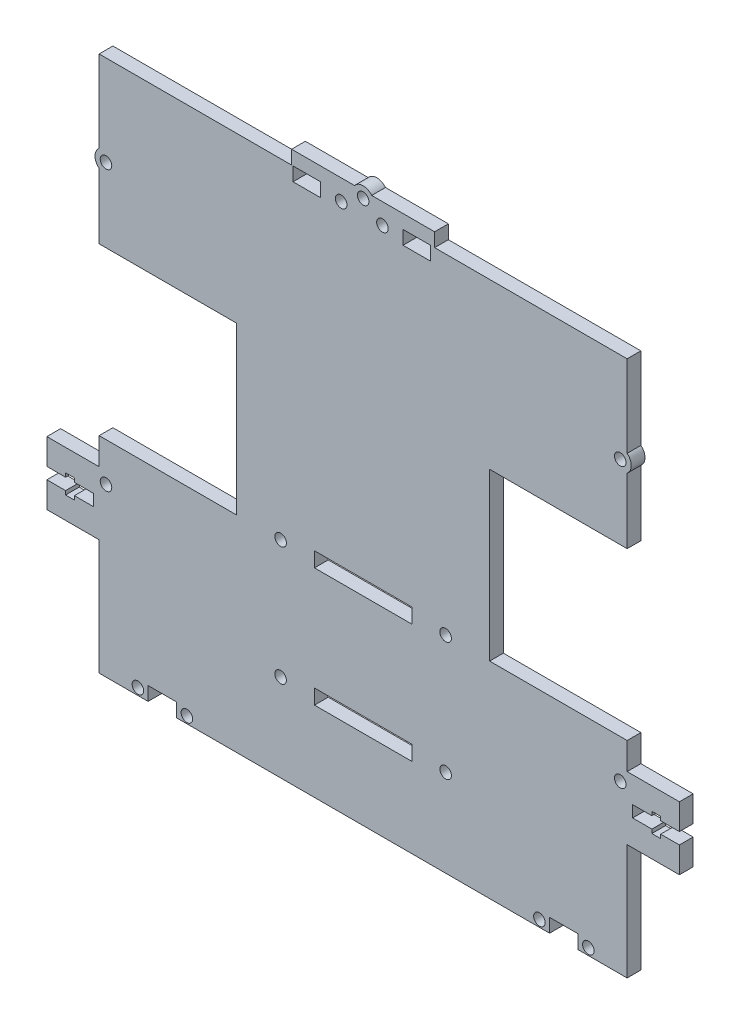
SolidWorks part; units mm, degrees
ref_plane "Front Plane" through (0, 0, 0) normal (0, 0, 1) x (1, 0, 0)
ref_plane "Top Plane" through (0, 0, 0) normal (0, 1, 0) x (1, 0, 0)
ref_plane "Right Plane" through (0, 0, 0) normal (1, 0, 0) x (0, 0, -1)
sketch "Sketch1" plane through (0, 0, 0) normal (0, 0, 1) x (1, 0, 0)
  line L0 (0, -36.0225) -> (0, -131.1775)
  line L1 (0, 0) -> (70, 0)
  line L2 (0, 0) -> (0, -29.7775)
  line L3 (0, -195) -> (192, -195)
  line L4 (192, 0) -> (192, -29.7775)
  line L5 (0, -60) -> (50, -60)
  line L6 (0, -60) -> (0, -120)
  line L7 (0, -120) -> (50, -120)
  line L8 (50, -60) -> (50, -120)
  line L9 (0, 0) -> (59, 0)
  line L10 (0, 0) -> (0, -21)
  line L14 (70, 0) -> (70, 5)
  line L15 (99.1225, 5) -> (122, 5)
  line L16 (122, 0) -> (122, 5)
  line L17 (192, -60) -> (142, -60)
  line L18 (192, -60) -> (192, -120)
  line L19 (192, -120) -> (142, -120)
  line L20 (142, -60) -> (142, -120)
  line L21 (0, -137.4225) -> (0, -195)
  line L22 (96, -1.5) -> (96, -63.5572) construction
  line L23 (192, -36.0225) -> (192, -131.1775)
  line L24 (192, -137.4225) -> (192, -195)
  line L26 (142, -120) -> (142, -195) construction
  line L27 (122, 0) -> (192, 0)
  line L28 (92.8775, 5) -> (70, 5)
  circle A0 centre (2.5, -32.9) radius 2.1
  arc A1 (0, -29.7775) -> (0, -36.0225) centre (2.5, -32.9) ccw
  circle A2 centre (2.5, -134.3) radius 2.1
  arc A3 (0, -131.1775) -> (0, -137.4225) centre (2.5, -134.3) ccw
  arc A4 (192, -131.1775) -> (192, -137.4225) centre (189.5, -134.3) cw
  arc A5 (192, -29.7775) -> (192, -36.0225) centre (189.5, -32.9) cw
  circle A6 centre (189.5, -32.9) radius 2.1
  circle A7 centre (189.5, -134.3) radius 2.1
  circle A8 centre (96, 2.5) radius 2.1
  arc A9 (99.1225, 5) -> (92.8775, 5) centre (96, 2.5) ccw
  point P20 (142, -90)
  point P22 (50, -90)
  dimension "D11" = 32.9
  dimension "D12" = 4.2
  dimension "D13" = 2.5
  dimension "D14" = 4
  dimension "D16" = 4.2
  dimension "D17" = 2.5
  dimension "D18" = 8
  dimension "D20" = 4.2
  dimension "D21" = 2.5
  dimension "D22" = 26
  dimension "D23" = 8
  dimension "D1" = 52
  dimension "D2" = 192
  dimension "D3" = 195
  dimension "D4" = 60
  dimension "D5" = 60
  dimension "D6" = 50
  dimension "D7" = 50
  dimension "D10" = 5
  dimension "D15" = 60.7
  dimension "D19" = 70
  dimension "D24" = 75
extrude "Boss-Extrude1" add sketch "Sketch1" along normal blind 5
ref_plane "Plane1" through (96, 0, 0) normal (1, 0, 0) x (0, 0, -1)
sketch "Sketch5" plane through (0, 0, 5) normal (0, 0, 1) x (1, 0, 0)
  line L8 (78.5, -165.718) -> (113.5, -165.718)
  line L9 (113.5, -165.718) -> (113.5, -160.718)
  line L10 (113.5, -160.718) -> (78.5, -160.718)
  line L11 (78.5, -160.718) -> (78.5, -165.718)
  line L12 (78.5, -122.5) -> (113.5, -122.5)
  line L13 (113.5, -122.5) -> (113.5, -117.5)
  line L14 (113.5, -117.5) -> (78.5, -117.5)
  line L15 (78.5, -117.5) -> (78.5, -122.5)
  line L16 (96, -122.5) -> (96, -141.0071) construction
  line L17 (28, -195) -> (18, -195)
  line L18 (28, -195) -> (28, -190)
  line L19 (28, -190) -> (18, -190)
  line L20 (18, -195) -> (18, -190)
  line L21 (164, -190) -> (174, -190)
  line L22 (174, -195) -> (174, -190)
  line L23 (164, -195) -> (174, -195)
  line L24 (164, -195) -> (164, -190)
  line L26 (96, -2.75) -> (96, 2.75) construction
  point P19 (96, -160.718)
  point P22 (96, -117.5)
  dimension "D1" = 5
  dimension "D2" = 10
  dimension "D3" = 35
extrude "Cut-Extrude2" cut sketch "Sketch5" against normal blind 5
sketch "Sketch6" plane through (0, 0, 5) normal (0, 0, 1) x (1, 0, 0)
  line L0 (215.5122, -18.3401) -> (215.5122, -25.8401) construction
  line L1 (174, -195) -> (174, -190) construction
  line L2 (174, -195) -> (192, -195) construction
  line L3 (169, -195) -> (169, -185.0635) construction
  line L4 (164, -195) -> (174, -195) construction
  line L5 (96, -195) -> (96, -179.8197) construction
  line L6 (28, -195) -> (164, -195) construction
  line L7 (23, -195) -> (23, -185.0635) construction
  line L8 (210.5122, -40.8401) -> (215.5122, -40.8401) construction
  line L9 (113.5, -117.5) -> (113.5, -122.5) construction
  line L10 (78.5, -122.5) -> (113.5, -122.5) construction
  line L11 (96, -117.5) -> (96, -106.4051) construction
  line L12 (113.5, -117.5) -> (78.5, -117.5) construction
  line L13 (113.5, -165.718) -> (78.5, -165.718) construction
  line L14 (113.5, -165.718) -> (113.5, -160.718) construction
  circle A0 centre (213.0122, -33.3401) radius 2.1
  circle A1 centre (177.9, -192.5) radius 2.1
  circle A2 centre (160.1, -192.5) radius 2.1
  circle A3 centre (-21.0122, -33.3401) radius 2.1
  circle A4 centre (31.9, -192.5) radius 2.1
  circle A5 centre (14.1, -192.5) radius 2.1
  circle A6 centre (126, -120) radius 2.1
  circle A7 centre (126, -163.218) radius 2.1
  circle A8 centre (66, -163.218) radius 2.1
  circle A9 centre (66, -120) radius 2.1
  dimension "D1" = 4.2
  dimension "D2" = 2.5
  dimension "D3" = 4.2
  dimension "D4" = 3.9
  dimension "D5" = 2.5
  dimension "D6" = 7.5
  dimension "D7" = 12.5
  dimension "D8" = 2.5
  dimension "D9" = 4.2
  dimension "D10" = 2.5
  dimension "D11" = 12.5
  dimension "D12" = 4.2
extrude "Cut-Extrude3" cut sketch "Sketch6" against normal blind 5
sketch "Sketch8" plane through (0, 0, 5) normal (0, 0, 1) x (1, 0, 0)
  line L0 (70.5122, 0) -> (80.5122, 0) construction
  line L1 (80.5122, 0) -> (80.5122, -5) construction
  line L2 (80.5122, -5) -> (70.5122, -5) construction
  line L3 (70.5122, -5) -> (70.5122, 0) construction
  line L4 (110.5122, 0) -> (120.5122, 0) construction
  line L5 (120.5122, 0) -> (120.5122, -5) construction
  line L6 (120.5122, -5) -> (110.5122, -5) construction
  line L7 (110.5122, -5) -> (110.5122, 0) construction
  line L8 (70.5122, 0) -> (80.5122, 0)
  line L9 (80.5122, 0) -> (80.5122, -5)
  line L10 (80.5122, -5) -> (70.5122, -5)
  line L11 (70.5122, -5) -> (70.5122, 0)
  line L12 (110.5122, 0) -> (120.5122, 0)
  line L13 (120.5122, 0) -> (120.5122, -5)
  line L14 (120.5122, -5) -> (110.5122, -5)
  line L15 (110.5122, -5) -> (110.5122, 0)
  line L16 (110.5122, -2.5) -> (80.5122, -2.5) construction
  circle A0 centre (88.0122, -2.5) radius 2.1
  circle A1 centre (103.0122, -2.5) radius 2.1
  dimension "D1" = 22.5
  dimension "D2" = 22.5
  dimension "D3" = 4.2
  dimension "D4" = 4.2
extrude "Cut-Extrude4" cut sketch "Sketch8" against normal blind 5
sketch "Sketch9" plane through (0, 0, 5) normal (0, 0, 1) x (1, 0, 0)
  line L0 (-19, -130) -> (0, -130)
  line L1 (5.9822, -130) -> (-34.0178, -130) construction
  line L3 (0, -153) -> (-19, -153)
  line L4 (-19, -130) -> (-19, -153)
  line L33 (192, -29.7775) -> (192, 0)
  line L35 (0, 0) -> (0, -29.7775)
  line L44 (164, -195) -> (164, -190)
  line L45 (164, -190) -> (174, -190)
  line L46 (174, -190) -> (174, -195)
  line L47 (174, -195) -> (192, -195)
  line L48 (192, -195) -> (192, -137.4225)
  line L49 (192, -131.1775) -> (192, -120)
  line L50 (192, -120) -> (142, -120)
  line L51 (142, -120) -> (142, -60)
  line L52 (142, -60) -> (192, -60)
  line L53 (192, -60) -> (192, -36.0225)
  line L61 (192, 0) -> (122, 0)
  line L62 (122, 0) -> (122, 5)
  line L63 (122, 5) -> (99.1225, 5)
  line L64 (92.8775, 5) -> (70, 5)
  line L65 (70, 5) -> (70, 0)
  line L66 (70, 0) -> (0, 0)
  line L77 (0, -36.0225) -> (0, -60)
  line L78 (0, -60) -> (50, -60)
  line L79 (50, -60) -> (50, -120)
  line L80 (50, -120) -> (0, -120)
  line L81 (0, -120) -> (0, -131.1775)
  line L82 (0, -137.4225) -> (0, -195)
  line L83 (0, -195) -> (18, -195)
  line L84 (18, -195) -> (18, -190)
  line L85 (18, -190) -> (28, -190)
  line L86 (28, -190) -> (28, -195)
  line L87 (28, -195) -> (164, -195)
  line L125 (0, -130) -> (0, -131.1775)
  line L126 (0, -137.4225) -> (0, -153)
  arc A3 (192, -137.4225) -> (192, -131.1775) centre (189.5, -134.3) ccw
  arc A4 (99.1225, 5) -> (92.8775, 5) centre (96, 2.5) ccw
  arc A5 (0, -131.1775) -> (0, -137.4225) centre (2.5, -134.3) ccw
  arc A8 (0, -131.1775) -> (0, -137.4225) centre (2.5, -134.3) ccw
  arc A11 (192, -36.0225) -> (192, -29.7775) centre (189.5, -32.9) ccw
  arc A13 (0, -29.7775) -> (0, -36.0225) centre (2.5, -32.9) ccw
  dimension "D2" = 23
  dimension "D3" = 19
  dimension "D1" = 0
extrude "Boss-Extrude3" add sketch "Sketch9" against normal blind 5
sketch "Sketch12" plane through (0, 0, 5) normal (0, 0, 1) x (1, 0, 0)
  line L0 (28, -195) -> (164, -195) construction
  line L1 (17.8, -190) -> (28.2, -190)
  line L2 (17.8, -190) -> (17.8, -195)
  line L3 (17.8, -195) -> (28.2, -195)
  line L4 (28.2, -190) -> (28.2, -195)
  line L5 (18, -190) -> (18, -195) construction
  line L6 (96, -122.5) -> (96, -128.3918) construction
  line L8 (163.8, -190) -> (163.8, -195)
  line L9 (174.2, -195) -> (163.8, -195)
  line L10 (174.2, -190) -> (174.2, -195)
  line L11 (174.2, -190) -> (163.8, -190)
  line L12 (28, -190) -> (18, -190) construction
  line L13 (96, -2.75) -> (96, 2.75) construction
  point P18 (0, 0)
  dimension "D1" = 10.4
  dimension "D2" = 0.2
extrude "Cut-Extrude5" cut sketch "Sketch12" against normal blind 5
sketch "Sketch13" plane through (0, 0, 5) normal (0, 0, 1) x (1, 0, 0)
  line L0 (78.5, -122.5) -> (113.5, -122.5) construction
  line L1 (78.3, -117.3) -> (113.7, -117.3)
  line L2 (78.3, -117.3) -> (78.3, -122.7)
  line L3 (78.3, -122.7) -> (113.7, -122.7)
  line L4 (113.7, -117.3) -> (113.7, -122.7)
  line L5 (78.5, -117.5) -> (78.5, -122.5) construction
  line L6 (113.5, -122.5) -> (113.5, -160.718) construction
  line L7 (113.5, -141.609) -> (102.679, -141.609) construction
  line L8 (113.7, -165.918) -> (113.7, -160.518)
  line L9 (78.3, -160.518) -> (113.7, -160.518)
  line L10 (78.3, -165.918) -> (78.3, -160.518)
  line L11 (78.3, -165.918) -> (113.7, -165.918)
  dimension "D1" = 5.4
  dimension "D2" = 35.4
  dimension "D3" = 0.2
  dimension "D4" = 0.2
extrude "Cut-Extrude6" cut sketch "Sketch13" against normal blind 5
sketch "Sketch16" plane through (0, 0, 5) normal (0, 0, 1) x (1, 0, 0)
  line L0 (96, 2.5) -> (96, -27.8276) construction
  line L1 (0, -59.8) -> (50, -59.8)
  line L2 (0, -59.8) -> (0, -120.2)
  line L3 (0, -120.2) -> (50, -120.2)
  line L5 (50, -59.8) -> (50, -120.2)
  line L8 (142, -59.8) -> (142, -120.2)
  line L9 (192, -120.2) -> (142, -120.2)
  line L10 (192, -59.8) -> (192, -120.2)
  line L11 (192, -59.8) -> (142, -59.8)
  line L43 (174.2, -190) -> (174.2, -195)
  line L44 (192, -29.7775) -> (192, 0)
  line L45 (192, -29.7775) -> (192, 0)
  line L46 (0, 0) -> (0, -29.7775)
  line L47 (0, 0) -> (0, -29.7775)
  line L48 (174.2, -195) -> (192, -195)
  line L49 (28.2, -195) -> (163.8, -195)
  line L53 (17.8, -195) -> (17.8, -190)
  line L54 (17.8, -190) -> (28.2, -190)
  line L55 (28.2, -190) -> (28.2, -195)
  line L59 (163.8, -195) -> (163.8, -190)
  line L60 (163.8, -190) -> (174.2, -190)
  line L64 (192, -195) -> (192, -137.4225)
  line L65 (192, -131.1775) -> (192, -120)
  line L66 (192, -120) -> (142, -120)
  line L67 (142, -120) -> (142, -60)
  line L68 (142, -60) -> (192, -60)
  line L69 (192, -60) -> (192, -36.0225)
  line L75 (0, -130) -> (-19, -130)
  line L76 (-19, -130) -> (-19, -153)
  line L77 (-19, -153) -> (0, -153)
  line L78 (192, 0) -> (122, 0)
  line L79 (122, 0) -> (122, 5)
  line L80 (122, 5) -> (99.1225, 5)
  line L81 (92.8775, 5) -> (70, 5)
  line L82 (70, 5) -> (70, 0)
  line L83 (70, 0) -> (0, 0)
  line L95 (0, -36.0225) -> (0, -60)
  line L96 (0, -60) -> (50, -60)
  line L97 (50, -60) -> (50, -120)
  line L98 (50, -120) -> (0, -120)
  line L99 (0, -120) -> (0, -130)
  line L103 (0, -153) -> (0, -195)
  line L104 (0, -195) -> (17.8, -195)
  line L118 (192, -120.2) -> (192, -120)
  line L120 (142, -120) -> (142, -60)
  line L148 (0, -59.8) -> (0, -60)
  arc A11 (192, -137.4225) -> (192, -131.1775) centre (189.5, -134.3) ccw
  arc A13 (99.1225, 5) -> (92.8775, 5) centre (96, 2.5) ccw
  arc A20 (192, -36.0225) -> (192, -29.7775) centre (189.5, -32.9) ccw
  arc A21 (192, -36.0225) -> (192, -29.7775) centre (189.5, -32.9) ccw
  arc A22 (0, -29.7775) -> (0, -36.0225) centre (2.5, -32.9) ccw
  arc A23 (0, -29.7775) -> (0, -36.0225) centre (2.5, -32.9) ccw
  dimension "D2" = 60.4
  dimension "D4" = 50
  dimension "D1" = 0
extrude "Cut-Extrude8" cut sketch "Sketch16" against normal blind 5 contours L5 L1 L2 L3 | L10 L11 L8 L9
ref_plane "Plane4" through (96, 0, 0) normal (1, 0, 0) x (0, 0, -1)
mirror "Mirror2" about plane through (96, 0, 0) normal (1, 0, 0) of "Boss-Extrude3"
sketch "Sketch17" plane through (0, 0, 5) normal (0, 0, 1) x (1, 0, 0)
  line L0 (211, -130) -> (211, -153) construction
  line L1 (211, -139.4) -> (194, -139.4)
  line L2 (211, -139.4) -> (211, -143.6)
  line L3 (211, -143.6) -> (194, -143.6)
  line L4 (194, -139.4) -> (194, -143.6)
  line L5 (211, -153) -> (192, -153) construction
  line L6 (201, -145) -> (204.2, -145)
  line L7 (201, -145) -> (201, -138)
  line L8 (201, -138) -> (204.2, -138)
  line L9 (204.2, -145) -> (204.2, -138)
  line L10 (96, -122.7) -> (96, -138) construction
  line L11 (78.3, -122.7) -> (113.7, -122.7) construction
  line L12 (-12.2, -145) -> (-12.2, -138)
  line L13 (-9, -138) -> (-12.2, -138)
  line L14 (-9, -145) -> (-9, -138)
  line L15 (-9, -145) -> (-12.2, -145)
  line L16 (-2, -139.4) -> (-2, -143.6)
  line L17 (-19, -143.6) -> (-2, -143.6)
  line L18 (-19, -139.4) -> (-19, -143.6)
  line L19 (-19, -139.4) -> (-2, -139.4)
  point P10 (204.2, -141.5)
  point P11 (194, -141.5)
  dimension "D1" = 3.2
  dimension "D2" = 17
  dimension "D3" = 6.8
  dimension "D4" = 4.2
  dimension "D5" = 11.5
  dimension "D6" = 7
extrude "Cut-Extrude9" cut sketch "Sketch17" against normal blind 5 contours L9 L3 L2 L1 | L3 L9 L1 L7 | L1 L9 L8 L7 | L3 L7 L1 L4 | L6 L9 L3 L7 | L19 L18 L17 L12 | L12 L19 L14 L13 | L19 L12 L17 L14 | L19 L14 L17 L16 | L17 L12 L15 L14
sketch "Sketch18" plane through (0, 0, 5) normal (0, 0, 1) x (1, 0, 0)
  line L0 (0, -36.0225) -> (0, -59.8) construction
  line L1 (0, 0) -> (0, -29.7775) construction
  line L2 (0, -36.0225) -> (0, -44.9964)
  line L3 (0, -20.9892) -> (0, -29.7775)
  line L4 (0, -44.9964) -> (-9, -44.9964)
  line L5 (-9, -44.9964) -> (-9, -20.9892)
  line L6 (-9, -20.9892) -> (0, -20.9892)
  arc A0 (0, -29.7775) -> (0, -36.0225) centre (2.5, -32.9) ccw construction
  arc A1 (0, -29.7775) -> (0, -36.0225) centre (2.5, -32.9) ccw
  dimension "D1" = 9
